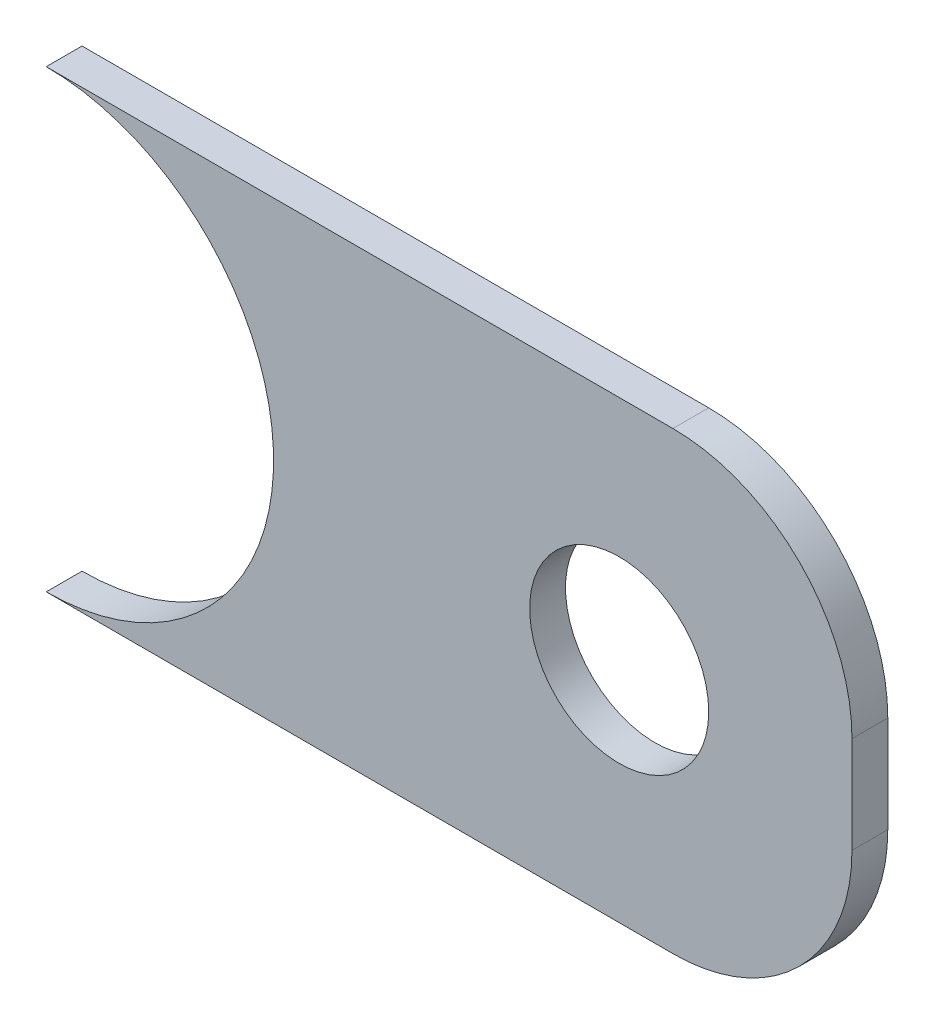
SolidWorks part; units mm, degrees
ref_plane "Front Plane" through (0, 0, 0) normal (0, 0, 1) x (1, 0, 0)
ref_plane "Top Plane" through (0, 0, 0) normal (0, 1, 0) x (1, 0, 0)
ref_plane "Right Plane" through (0, 0, 0) normal (1, 0, 0) x (0, 0, -1)
sketch "Sketch1" plane through (0, 0, 0) normal (0, 0, 1) x (1, 0, 0)
  line L1 (0, 12.7) -> (35, 12.7)
  line L3 (0, -12.7) -> (35, -12.7)
  line L4 (45, 2.7) -> (45, -2.7)
  arc A1 (0, -12.7) -> (0, 12.7) centre (0, 0) ccw
  circle A2 centre (32, 0) radius 5
  arc A3 (35, -12.7) -> (45, -2.7) centre (35, -2.7) ccw
  arc A4 (35, 12.7) -> (45, 2.7) centre (35, 2.7) cw
  point P11 (45, -12.7)
  dimension "D1" = 25.4
  dimension "D3" = 32
  dimension "D4" = 10
  dimension "D5" = 10
  dimension "D2" = 45
extrude "Boss-Extrude1" add sketch "Sketch1" along normal blind 2
